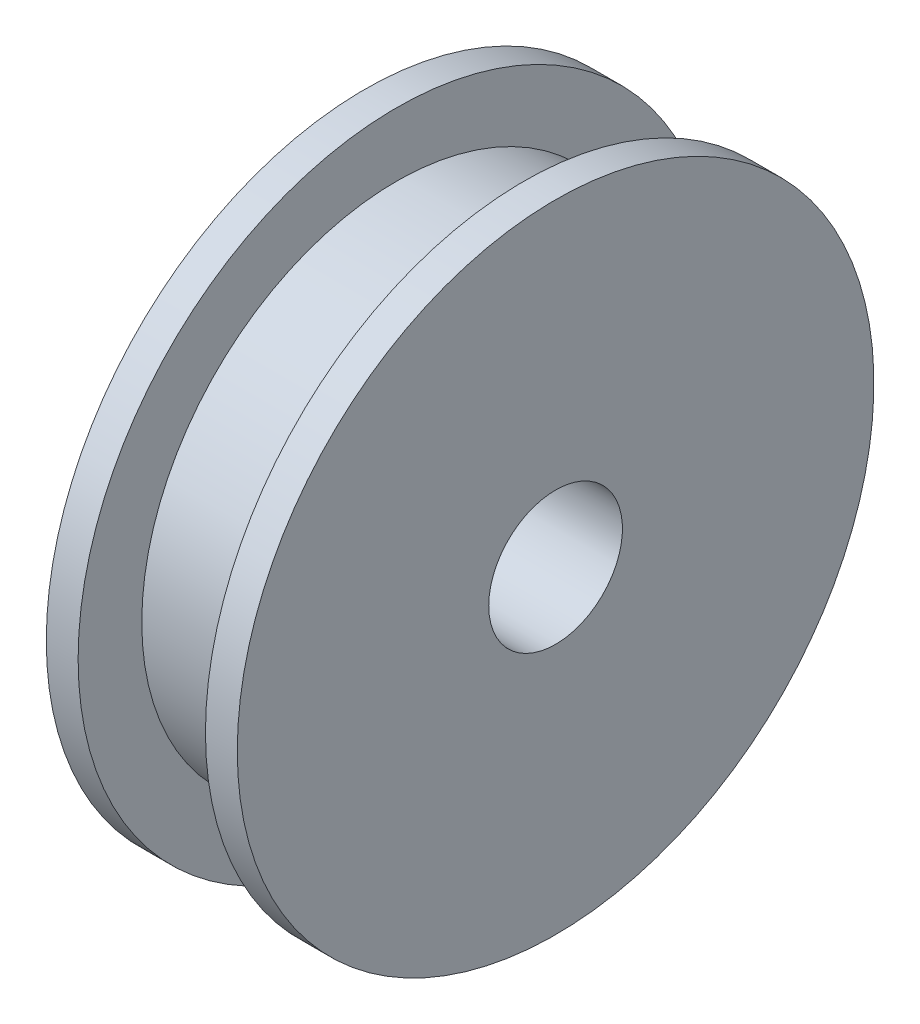
SolidWorks part; units mm, degrees
ref_plane "Plano frontal" through (0, 0, 0) normal (0, 0, 1) x (1, 0, 0)
ref_plane "Plano superior" through (0, 0, 0) normal (0, 1, 0) x (1, 0, 0)
ref_plane "Plano direito" through (0, 0, 0) normal (1, 0, 0) x (0, 0, -1)
sketch "Esboço1" plane through (0, 0, 0) normal (0, 0, 1) x (1, 0, 0)
  line L0 (0, 0) -> (7.1551, 0) construction
  line L1 (-1.5, 0) -> (-1.5, 5) construction
  line L2 (-1.5, 5) -> (-1, 5)
  line L3 (-1, 5) -> (-1, 4)
  line L4 (-1, 4) -> (1, 4)
  line L5 (1, 4) -> (1, 5)
  line L6 (1, 5) -> (1.5, 5)
  line L7 (1.5, 5) -> (1.5, 0) construction
  line L8 (1.5, 0) -> (-1.5, 0) construction
  line L9 (-1, 4) -> (1, 6) construction
  line L10 (-1, 4) -> (-1, 6) construction
  line L11 (1, 6) -> (-1, 6) construction
  line L12 (1, 6) -> (1, 4) construction
  line L13 (-1.5, 1.05) -> (1.5, 1.05)
  line L14 (-1.5, 5) -> (-1.5, 1.05)
  line L15 (1.5, 5) -> (1.5, 1.05)
  circle A0 centre (0, 5) radius 1
  point P5 (0, 5)
  point P18 (0, 0)
  dimension "D1" = 5
  dimension "D2" = 3
  dimension "D3" = 2
  dimension "D4" = 1
  dimension "D5" = 1.05
revolve "Revolução2" add sketch "Esboço1" angle 360 about L0
